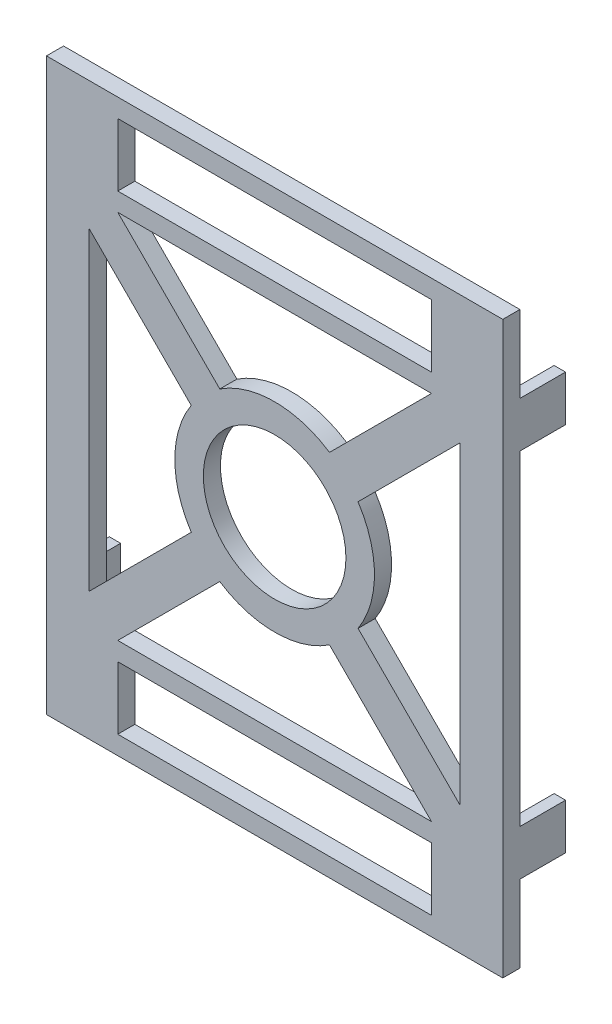
SolidWorks part; units mm, degrees
material "6061-T6 (SS)"
ref_plane "Front Plane" through (0, 0, 0) normal (0, 0, 1) x (1, 0, 0)
ref_plane "Top Plane" through (0, 0, 0) normal (0, 1, 0) x (1, 0, 0)
ref_plane "Right Plane" through (0, 0, 0) normal (1, 0, 0) x (0, 0, -1)
sketch "Sketch1" plane through (0, 0, 0) normal (0, 0, 1) x (1, 0, 0)
  line L0 (-62.1632, 0) -> (109.222, 0) construction
  line L1 (-40, 50) -> (40, 50)
  line L2 (-40, 50) -> (-40, -50)
  line L3 (-40, -50) -> (40, -50)
  line L4 (40, 50) -> (40, -50)
  line L5 (-40, 50) -> (40, -50) construction
  line L6 (-40, -50) -> (40, 50) construction
  line L7 (-27.5, 32.5) -> (27.5, 32.5)
  line L8 (-32.5, 27.5) -> (-32.5, -27.5299)
  line L9 (-27.5, -32.5) -> (27.5, -32.5)
  line L11 (-32.5, 32.5) -> (32.5, -32.5) construction
  line L12 (-32.5, -32.5) -> (32.5, 32.5) construction
  line L13 (0, 57.4573) -> (0, -57.4573) construction
  line L14 (-27.5, 35.727) -> (-27.5, -35.8487) construction
  line L15 (27.5, 35.727) -> (27.5, -35.8487) construction
  line L16 (27.5, -35.8487) -> (-27.5, -35.8487) construction
  line L17 (-27.5, 35.727) -> (27.5, 35.727) construction
  line L18 (-27.5, 32.5) -> (-9.6136, 14.6229)
  line L19 (-46.1023, 27.5) -> (46.1023, 27.5) construction
  line L20 (-46.1023, 27.5) -> (-46.1023, -27.5) construction
  line L21 (-46.1023, -27.5) -> (46.1023, -27.5) construction
  line L22 (46.1023, 27.5) -> (46.1023, -27.5) construction
  line L23 (-46.1023, 27.5) -> (46.1023, -27.5) construction
  line L24 (-46.1023, -27.5) -> (46.1023, 27.5) construction
  line L25 (-32.5, 27.5) -> (-14.6192, 9.6192)
  line L26 (27.5, 32.5) -> (9.6246, 14.6157)
  line L27 (32.5, 27.5) -> (14.6192, 9.6192)
  line L32 (32.5, 27.5) -> (32.5, -27.5)
  line L33 (32.5, -27.5) -> (14.6279, -9.6059)
  line L34 (-27.5, -35.727) -> (27.5, -35.727)
  line L35 (-14.6109, -9.6319) -> (-32.5, -27.5299)
  line L36 (-9.6192, -14.6192) -> (-27.5, -32.5)
  line L37 (-27.5, 46.7392) -> (27.5, 46.7392)
  line L38 (-27.5, 46.7392) -> (-27.5, 35.727)
  line L39 (-27.5, 35.727) -> (27.5, 35.727)
  line L40 (9.6192, -14.6192) -> (27.5, -32.5)
  line L41 (27.5, 46.7392) -> (27.5, 35.727)
  line L42 (27.5, -46.7392) -> (27.5, -35.727)
  line L43 (-27.5, -46.7392) -> (27.5, -46.7392)
  line L44 (-27.5, -46.7392) -> (-27.5, -35.727)
  circle A0 centre (0, 0) radius 12.5
  arc A1 (-14.6192, 9.6192) -> (-14.6109, -9.6319) centre (0, 0) ccw
  arc A2 (9.6246, 14.6157) -> (-9.6136, 14.6229) centre (0, 0) ccw
  arc A3 (-9.6192, -14.6192) -> (9.6192, -14.6192) centre (0, 0) ccw
  arc A4 (14.6279, -9.6059) -> (14.6192, 9.6192) centre (0, 0) ccw
  point P0 (0, 0)
  dimension "D3" = 25
  dimension "D4" = 35
  dimension "D1" = 80
  dimension "D2" = 100
  dimension "D5" = 65
  dimension "D6" = 65
  dimension "D7" = 5
  dimension "D9" = 55
  dimension "D10" = 55
  dimension "D11" = 5
extrude "Boss-Extrude4" add sketch "Sketch1" along normal blind 3
sketch "Sketch4" plane through (0, 0, 0) normal (0, 0, -1) x (-1, 0, 0)
  line L0 (-27.5, 32.5) -> (-49.8937, 32.5) construction
  line L1 (-40, 36.5) -> (-40, 28.5)
  line L2 (-40, -50) -> (-40, 50) construction
  line L3 (-40, 28.5) -> (-38, 28.5)
  line L4 (-38, 28.5) -> (-38, 36.5)
  line L5 (-38, 36.5) -> (-40, 36.5)
  line L6 (-52.4011, 0) -> (61.9846, 0) construction
  line L7 (0, 42.388) -> (0, -43.6264) construction
  line L8 (-38, -28.5) -> (-38, -36.5)
  line L9 (-40, -28.5) -> (-38, -28.5)
  line L10 (-40, -36.5) -> (-40, -28.5)
  line L11 (-38, -36.5) -> (-40, -36.5)
  line L12 (38, 28.5) -> (38, 36.5)
  line L13 (40, 28.5) -> (38, 28.5)
  line L14 (40, 36.5) -> (40, 28.5)
  line L15 (38, 36.5) -> (40, 36.5)
  line L16 (40, -28.5) -> (38, -28.5)
  line L17 (40, -36.5) -> (40, -28.5)
  line L18 (38, -36.5) -> (40, -36.5)
  line L19 (38, -28.5) -> (38, -36.5)
  dimension "D1" = 8
  dimension "D2" = 4
  dimension "D3" = 2
extrude "Boss-Extrude7" add sketch "Sketch4" along normal blind 8
